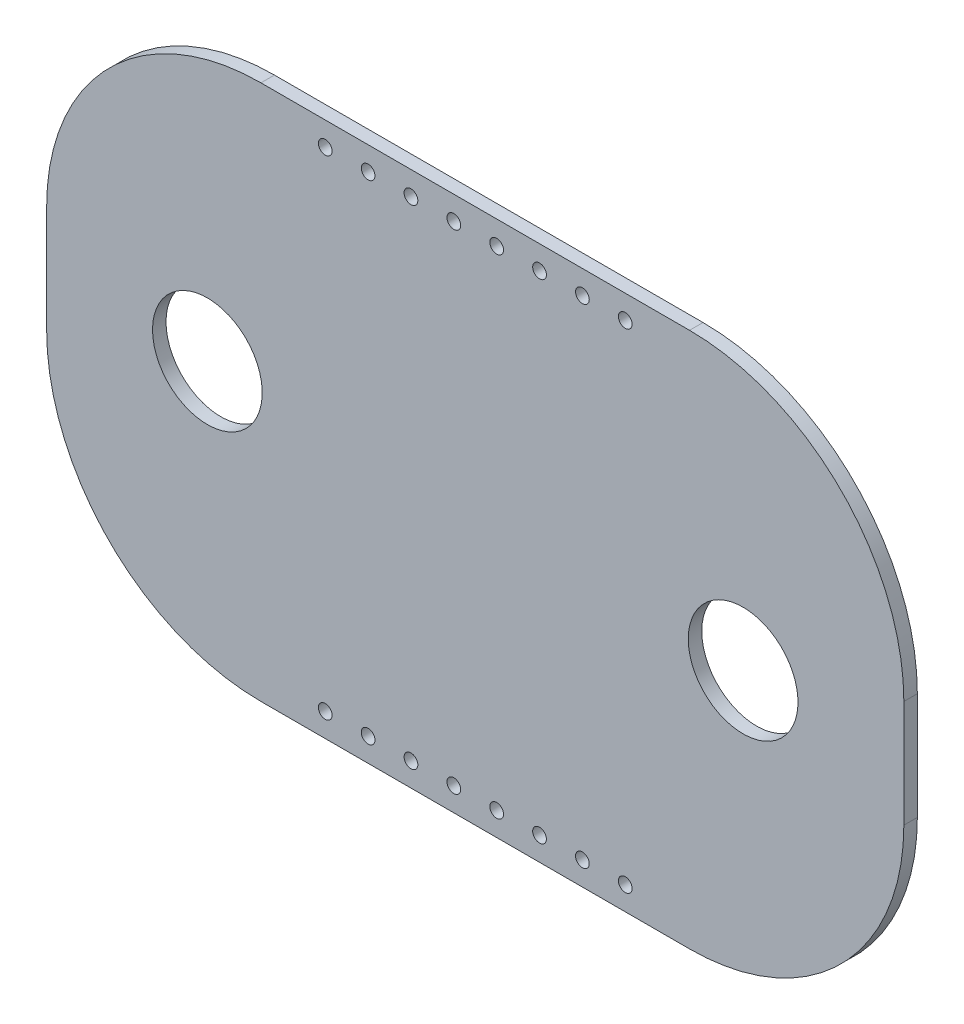
SolidWorks part; units mm, degrees
ref_plane "Front Plane" through (0, 0, 0) normal (0, 0, 1) x (1, 0, 0)
ref_plane "Top Plane" through (0, 0, 0) normal (0, 1, 0) x (1, 0, 0)
ref_plane "Right Plane" through (0, 0, 0) normal (1, 0, 0) x (0, 0, -1)
sketch "Sketch1" plane through (0, 0, 0) normal (0, 0, 1) x (1, 0, 0)
  line L0 (-15.875, 15.875) -> (47.625, 15.875) construction
  line L3 (0, 31.75) -> (31.75, 31.75)
  line L5 (0, 0) -> (31.75, 0)
  line L7 (15.875, 31.75) -> (15.875, 0) construction
  line L8 (3.175, 31.75) -> (28.575, 31.75)
  line L9 (-9.525, 12.7) -> (-9.525, 19.05)
  line L10 (28.575, 0) -> (3.175, 0)
  line L12 (41.275, 19.05) -> (41.275, 12.7)
  arc A38 (41.275, 12.7) -> (28.575, 0) centre (28.575, 12.7) cw
  arc A39 (28.575, 31.75) -> (41.275, 19.05) centre (28.575, 19.05) cw
  arc A40 (0, 31.75) -> (0, 0) centre (0, 15.875) ccw
  arc A41 (31.75, 0) -> (31.75, 31.75) centre (31.75, 15.875) ccw
  circle A42 centre (0, 15.875) radius 3.2512
  circle A43 centre (31.75, 15.875) radius 3.2512
  arc A44 (-9.525, 19.05) -> (3.175, 31.75) centre (3.175, 19.05) cw
  arc A45 (-9.525, 12.7) -> (3.175, 0) centre (3.175, 12.7) ccw
  point P29 (0, 15.875)
  dimension "D2" = 31.75
  dimension "D4" = 6.5024
  dimension "D5" = 50.8
  dimension "D6" = 25.4
  dimension "D1" = 31.75
  dimension "D3" = 6.5024
  dimension "D7" = 12.7
extrude "Boss-Extrude1" add sketch "Sketch1" along normal blind 0.8
sketch "Sketch3" plane through (0, 0, 0.8) normal (0, 0, -1) x (-1, 0, 0)
  line L0 (-3.175, 0) -> (-28.575, 0) construction
  line L2 (-3.175, 31.75) -> (-28.575, 31.75) construction
  line L3 (-3.175, 0) -> (-28.575, 0)
  line L4 (-3.175, 31.75) -> (-28.575, 31.75)
  line L5 (-15.875, 31.75) -> (-15.875, 0) construction
  line L6 (0, 15.875) -> (-33.3089, 15.875) construction
  circle A16 centre (-14.605, 30.353) radius 0.4064
  circle A17 centre (-12.065, 30.353) radius 0.4064
  circle A18 centre (-9.525, 30.353) radius 0.4064
  circle A19 centre (-6.985, 30.353) radius 0.4064
  circle A20 centre (-24.765, 30.353) radius 0.4064
  circle A21 centre (-22.225, 30.353) radius 0.4064
  circle A22 centre (-19.685, 30.353) radius 0.4064
  circle A23 centre (-17.145, 30.353) radius 0.4064
  circle A24 centre (-17.145, 1.397) radius 0.4064
  circle A25 centre (-19.685, 1.397) radius 0.4064
  circle A26 centre (-22.225, 1.397) radius 0.4064
  circle A27 centre (-24.765, 1.397) radius 0.4064
  circle A28 centre (-6.985, 1.397) radius 0.4064
  circle A29 centre (-9.525, 1.397) radius 0.4064
  circle A30 centre (-12.065, 1.397) radius 0.4064
  circle A31 centre (-14.605, 1.397) radius 0.4064
  dimension "D1" = 30.353
  dimension "D2" = 0.8128
  dimension "D3" = 1.27
extrude "Cut-Extrude3" cut sketch "Sketch3" along normal through all contours A19 | A18 | A17 | A16 | A23 | A22 | A21 | A20 | A28 | A29 | A30 | A31 | A24 | A25 | A26 | A27
